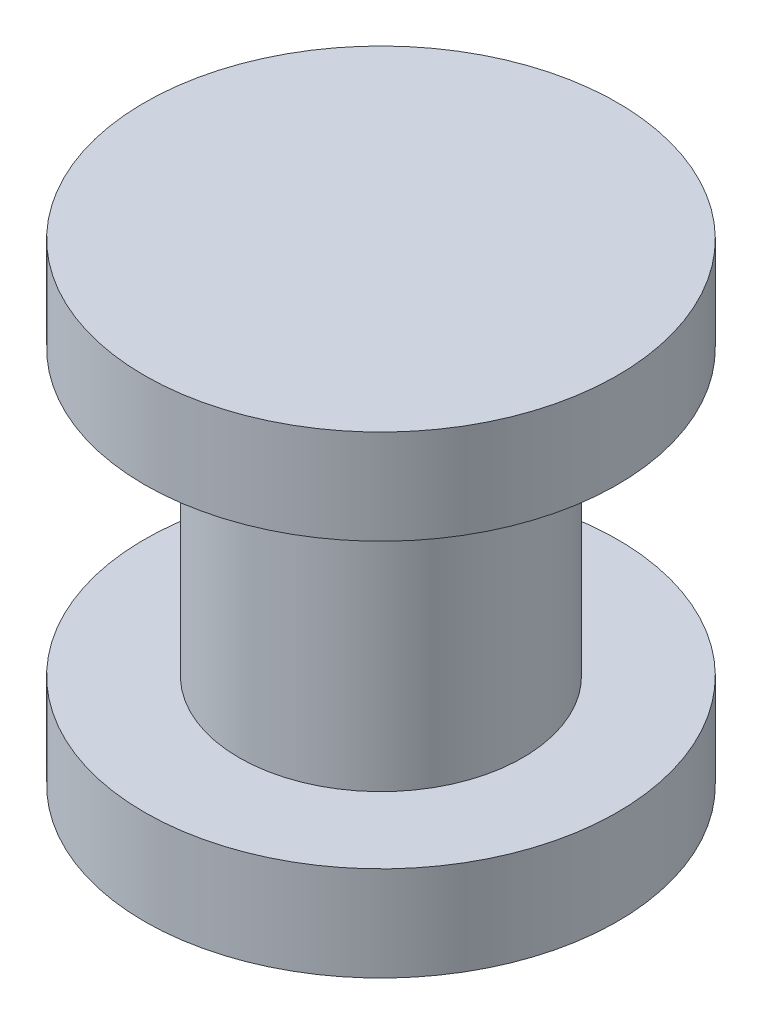
SolidWorks part; units mm, degrees
ref_plane "Front Plane" through (0, 0, 0) normal (0, 0, 1) x (1, 0, 0)
ref_plane "Top Plane" through (0, 0, 0) normal (0, 1, 0) x (1, 0, 0)
ref_plane "Right Plane" through (0, 0, 0) normal (1, 0, 0) x (0, 0, -1)
sketch "Sketch1" plane through (0, 0, 0) normal (0, 0, 1) x (1, 0, 0)
  line L0 (-14.7615, 24.9486) -> (-17.2615, 24.9486)
  line L1 (-14.7615, 24.9486) -> (-14.7615, 19.9486)
  line L2 (-14.7615, 19.9486) -> (-17.2615, 19.9486)
  line L3 (-17.2615, 19.9486) -> (-17.2615, 20.9486)
  line L4 (-17.2615, 20.9486) -> (-16.2615, 20.9486)
  line L5 (-16.2615, 20.9486) -> (-16.2615, 23.9486)
  line L6 (-16.2615, 23.9486) -> (-17.2615, 23.9486)
  line L7 (-17.2615, 23.9486) -> (-17.2615, 24.9486)
  line L8 (-14.7615, 24.9486) -> (-14.7615, 19.9486) construction
  dimension "D1" = 2.5
  dimension "D2" = 2.5
  dimension "D3" = 5
  dimension "D4" = 1.5
  dimension "D5" = 1
  dimension "D6" = 1
revolve "Revolve1" add sketch "Sketch1" angle 360 about L8
